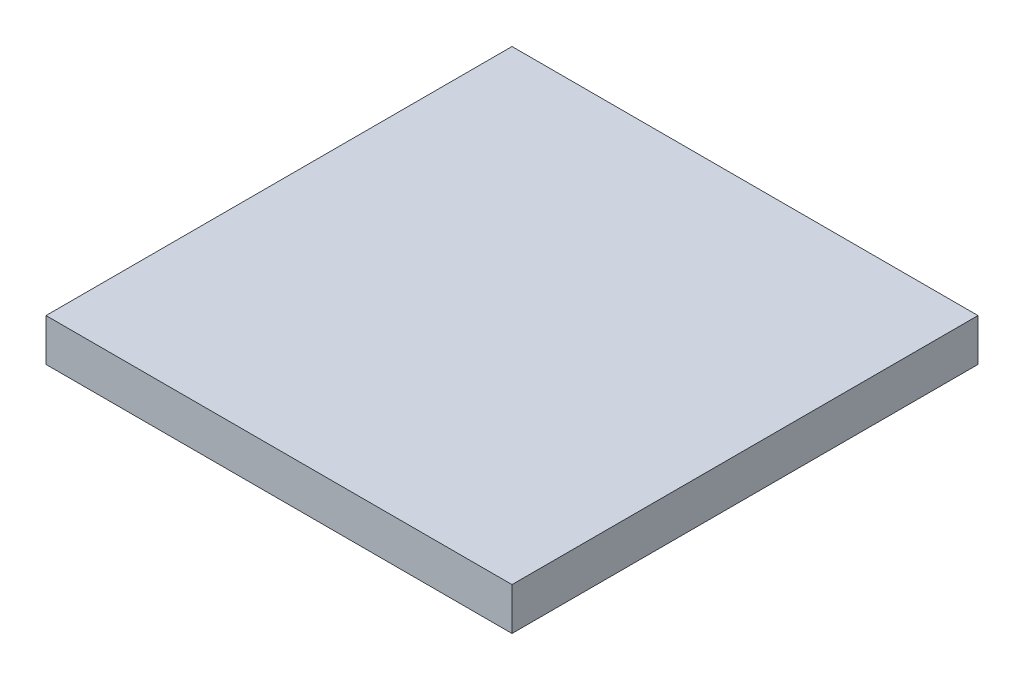
SolidWorks part; units mm, degrees
ref_plane "Front Plane" through (0, 0, 0) normal (0, 0, 1) x (1, 0, 0)
ref_plane "Top Plane" through (0, 0, 0) normal (0, 1, 0) x (1, 0, 0)
ref_plane "Right Plane" through (0, 0, 0) normal (1, 0, 0) x (0, 0, -1)
sketch "Sketch1" plane through (0, 0, 0) normal (0, 1, 0) x (1, 0, 0)
  line L1 (-275, -275) -> (275, -275)
  line L2 (-275, -275) -> (-275, 275)
  line L3 (-275, 275) -> (275, 275)
  line L4 (275, -275) -> (275, 275)
  line L5 (-275, -275) -> (275, 275) construction
  line L6 (-275, 275) -> (275, -275) construction
  point P0 (0, 0)
  dimension "D1" = 550
extrude "Boss-Extrude1" add sketch "Sketch1" against normal blind 50
sketch "Sketch2" plane through (0, 0, 0) normal (0, 1, 0) x (1, 0, 0)
  circle A0 centre (0, 0) radius 5
  dimension "D1" = 10
